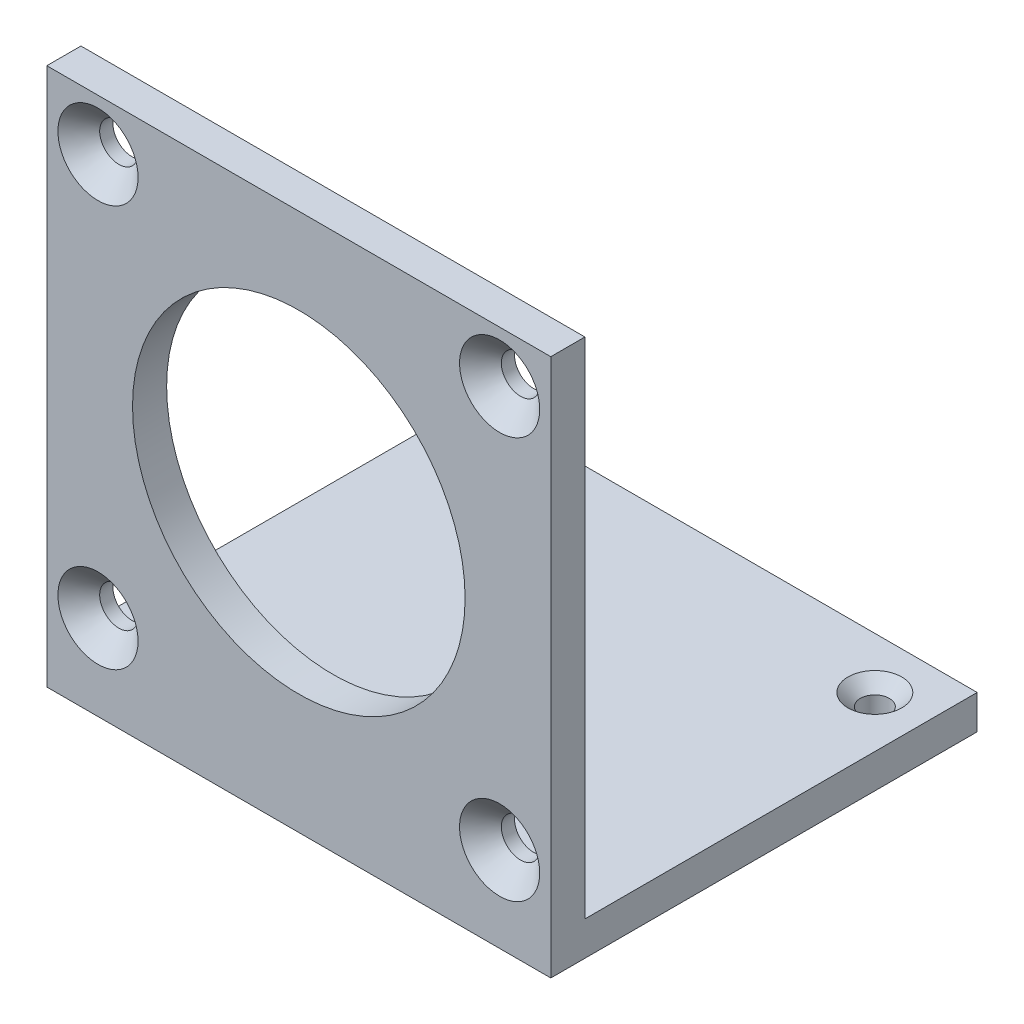
SolidWorks part; units mm, degrees
ref_plane "Front Plane" through (0, 0, 0) normal (0, 0, 1) x (1, 0, 0)
ref_plane "Top Plane" through (0, 0, 0) normal (0, 1, 0) x (1, 0, 0)
ref_plane "Right Plane" through (0, 0, 0) normal (1, 0, 0) x (0, 0, -1)
sketch "Sketch1" plane through (0, 0, 0) normal (0, 0, 1) x (1, 0, 0)
  line L0 (-6, -6) -> (53.1, -6)
  line L1 (0, 0) -> (47.1, 0) construction
  line L2 (0, 0) -> (0, 47.1) construction
  line L3 (0, 47.1) -> (47.1, 47.1) construction
  line L4 (47.1, 0) -> (47.1, 47.1) construction
  line L5 (53.1, -6) -> (53.1, 53.1)
  line L6 (-6, 53.1) -> (53.1, 53.1)
  line L7 (-6, -6) -> (-6, 53.1)
  circle A0 centre (23.55, 23.55) radius 19.5
  circle A1 centre (0, 47.1) radius 1.55
  circle A2 centre (47.1, 47.1) radius 1.55
  circle A3 centre (47.1, 0) radius 1.55
  circle A4 centre (0, 0) radius 1.55
  point P12 (23.55, 53.1)
  point P14 (53.1, 23.55)
  dimension "D4" = 39
  dimension "D5" = 3.1
  dimension "D2" = 47.1
  dimension "D3" = 6
extrude "Boss-Extrude1" add sketch "Sketch1" along normal blind 4
sketch "Sketch2" plane through (0, -6, 0) normal (0, -1, 0) x (1, 0, 0)
  line L5 (-6, 4) -> (53.1, 4)
  line L6 (-6, 4) -> (-6, -46)
  line L7 (-6, -46) -> (53.1, -46)
  line L8 (53.1, 4) -> (53.1, -46)
  circle A0 centre (0, -40) radius 1.5
  circle A1 centre (47.1, -40) radius 1.5
  circle A2 centre (23.55, -18) radius 1.5
  point P15 (23.55, -46)
  dimension "D2" = 3
  dimension "D3" = 6
  dimension "D4" = 6
  dimension "D5" = 22
  dimension "D6" = 6
  dimension "D1" = 50
extrude "Boss-Extrude2" add sketch "Sketch2" along normal blind 4
hole_wizard "CSK for M3 Flat Head Machine Screw1" positions "Sketch3" profile "Sketch4" countersink size "M3" standard "ANSI Metric" end condition through all
sketch "Sketch3" plane through (0, -6, 0) normal (0, 1, 0) x (1, 0, 0)
  point P0 (0, 40)
  point P3 (47.1, 40)
  point P6 (23.55, 18)
sketch "Sketch4" plane through (0, -6, -40) normal (1, 0, 0) x (0, 0, 1)
  line L0 (0, 0) -> (0, 4)
  line L1 (0, 4) -> (1.7, 4)
  line L2 (1.7, 4) -> (1.7, 1.45)
  line L3 (1.7, 1.45) -> (3.15, 0)
  line L5 (3.15, 0) -> (0, 0)
  line L6 (-1.7, 1.45) -> (-3.15, 0) construction
  line L11 (0, -6.35) -> (0, 107.95) construction
  dimension "Thru Hole Dia." = 3.4
  dimension "Thru Hole Depth" = 4
  dimension "Near C'Sink Dia." = 6.3
  dimension "Near C'Sink Angle" = 90
hole_wizard "CSK for M4 Flat Head Machine Screw1" positions "Sketch5" profile "Sketch6" countersink size "M4" standard "ANSI Metric" end condition through all
sketch "Sketch5" plane through (0, 0, 4) normal (0, 0, 1) x (1, 0, 0)
  point P0 (0, 47.1)
  point P3 (47.1, 47.1)
  point P6 (47.1, 0)
  point P9 (0, 0)
sketch "Sketch6" plane through (0, 47.1, 4) normal (1, 0, 0) x (0, -1, 0)
  line L0 (0, 0) -> (0, 50)
  line L1 (0, 50) -> (2.25, 50)
  line L2 (2.25, 50) -> (2.25, 2.45)
  line L3 (2.25, 2.45) -> (4.7, 0)
  line L5 (4.7, 0) -> (0, 0)
  line L6 (-2.25, 2.45) -> (-4.7, 0) construction
  line L11 (0, -6.35) -> (0, 107.95) construction
  dimension "Thru Hole Dia." = 4.5
  dimension "Thru Hole Depth" = 50
  dimension "Near C'Sink Dia." = 9.4
  dimension "Near C'Sink Angle" = 90
